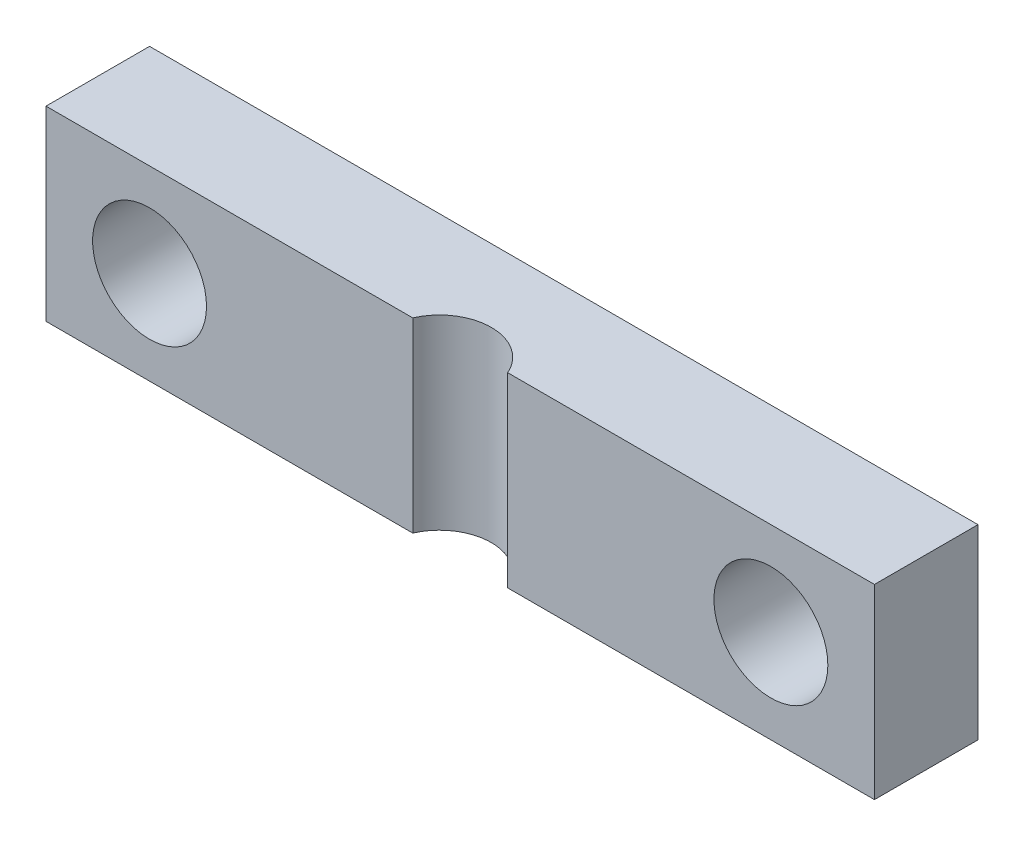
SolidWorks part; units mm, degrees
ref_plane "前视基准面" through (0, 0, 0) normal (0, 0, 1) x (1, 0, 0)
ref_plane "上视基准面" through (0, 0, 0) normal (0, 1, 0) x (1, 0, 0)
ref_plane "右视基准面" through (0, 0, 0) normal (1, 0, 0) x (0, 0, -1)
other "Configuration Table"
sketch "草图1" plane through (0, 0, 0) normal (0, 0, 1) x (1, 0, 0)
  line L1 (-20, 9) -> (20, 9)
  line L2 (-20, 9) -> (-20, 0)
  line L3 (-20, 0) -> (20, 0)
  line L4 (20, 9) -> (20, 0)
  dimension "D1" = 9
  dimension "D2" = 40
extrude "凸台-拉伸1" add sketch "草图1" along normal blind 5
sketch "草图2" plane through (0, 0, 5) normal (0, 0, 1) x (1, 0, 0)
  line L0 (-22.5659, 4.5) -> (24.1268, 4.5) construction
  line L1 (-20, 0) -> (20, 0) construction
  line L2 (20, 9) -> (-20, 9) construction
  line L3 (20, 0) -> (20, 9) construction
  line L4 (-20, 9) -> (-20, 0) construction
  circle A0 centre (15, 4.5) radius 2.75
  circle A1 centre (-15, 4.5) radius 2.75
  dimension "D1" = 5.5
  dimension "D2" = 5.5
  dimension "D3" = 5
  dimension "D4" = 5
extrude "切除-拉伸1" cut sketch "草图2" against normal blind 10
sketch "草图3" plane through (0, 9, 0) normal (0, 1, 0) x (1, 0, 0)
  line L0 (0, 0) -> (0, -9.7675) construction
  line L1 (20, -5) -> (-20, -5) construction
  circle A0 centre (0, -6) radius 2.5
  dimension "D1" = 5
  dimension "D2" = 1
extrude "切除-拉伸2" cut sketch "草图3" against normal blind 10
